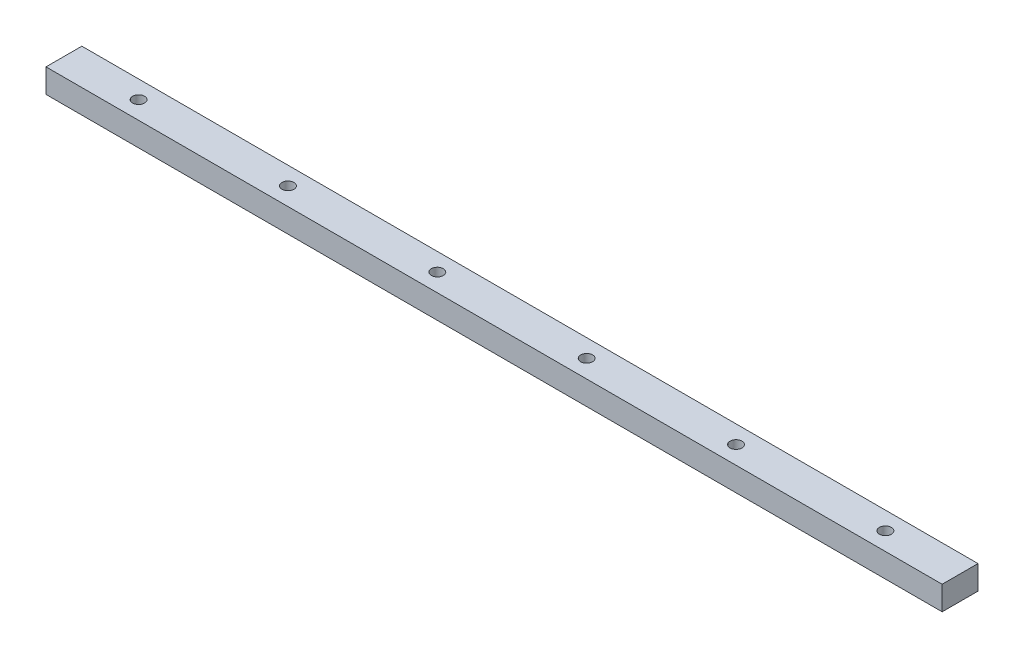
SolidWorks part; units mm, degrees
material "201 Annealed Stainless Steel (SS)"
ref_plane "Front Plane" through (0, 0, 0) normal (0, 0, 1) x (1, 0, 0)
ref_plane "Top Plane" through (0, 0, 0) normal (0, 1, 0) x (1, 0, 0)
ref_plane "Right Plane" through (0, 0, 0) normal (1, 0, 0) x (0, 0, -1)
sketch "Sketch2" plane through (0, 0, 0) normal (0, 1, 0) x (1, 0, 0)
  line L0 (-125, 0) -> (-75, 0) construction
  line L1 (-150, -6) -> (150, -6)
  line L2 (-150, -6) -> (-150, 6)
  line L3 (-150, 6) -> (150, 6)
  line L4 (150, -6) -> (150, 6)
  line L5 (-150, -6) -> (150, 6) construction
  line L6 (-150, 6) -> (150, -6) construction
  line L7 (-75, 0) -> (-25, 0) construction
  line L8 (-25, 0) -> (25, 0) construction
  line L9 (25, 0) -> (75, 0) construction
  line L10 (75, 0) -> (125, 0) construction
  circle A0 centre (-125, 0) radius 2
  circle A1 centre (-75, 0) radius 2
  circle A2 centre (-25, 0) radius 2
  circle A3 centre (25, 0) radius 2
  circle A4 centre (75, 0) radius 2
  circle A5 centre (125, 0) radius 2
  point P0 (0, 0)
  point P18 (0, 0)
  dimension "D4" = 4
  dimension "D1" = 300
  dimension "D2" = 12
  dimension "D3" = 50
extrude "Boss-Extrude1" add sketch "Sketch2" along normal mid plane 8
